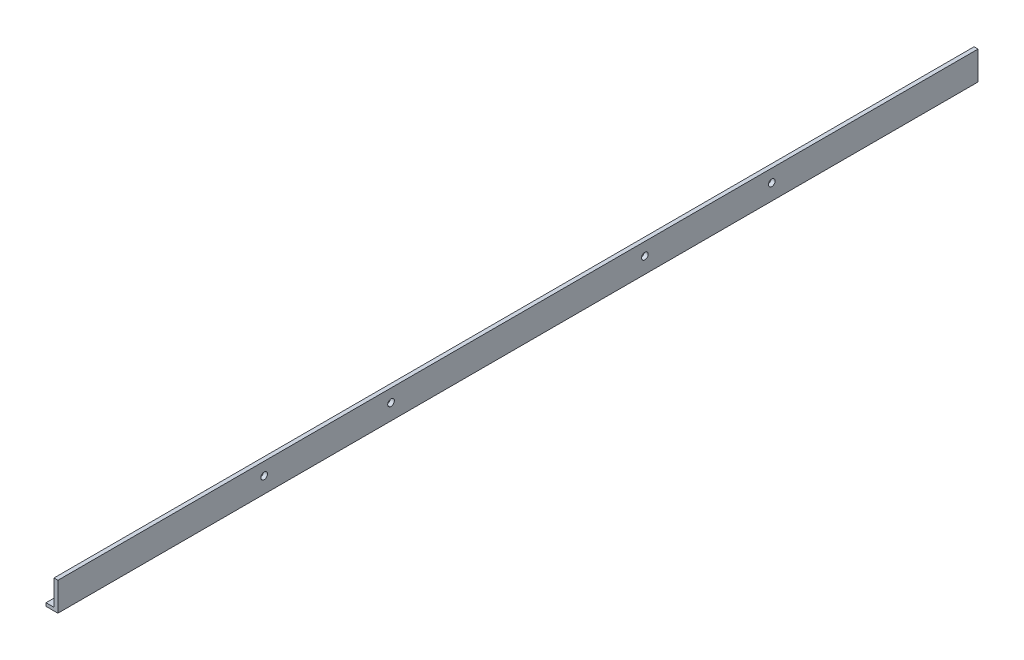
SolidWorks part; units mm, degrees
material "1.4511 (X3CrNb17)"
ref_plane "前视基准面" through (0, 0, 0) normal (0, 0, 1) x (1, 0, 0)
ref_plane "上视基准面" through (0, 0, 0) normal (0, 1, 0) x (1, 0, 0)
ref_plane "右视基准面" through (0, 0, 0) normal (1, 0, 0) x (0, 0, -1)
sketch "草图1" plane through (0, 0, 0) normal (0, 0, 1) x (1, 0, 0)
  line L0 (0, 0) -> (0, 18)
  line L1 (0, 18) -> (-2.5, 18)
  line L2 (-2.5, 18) -> (-2.5, 2)
  line L3 (-2.5, 2) -> (-7.5, 2)
  line L4 (-7.5, 2) -> (-7.5, 0)
  line L5 (-7.5, 0) -> (0, 0)
  dimension "D1" = 18
  dimension "D2" = 2.5
  dimension "D3" = 16
  dimension "D4" = 5
extrude "凸台-拉伸1" add sketch "草图1" along normal blind 580
sketch "草图2" plane through (-2.5, 0, 0) normal (-1, 0, 0) x (0, 0, 1)
  line L0 (290, 18) -> (290, 2) construction
  line L1 (580, 18) -> (0, 18) construction
  line L2 (580, 2) -> (0, 2) construction
  line L3 (130, 10) -> (450, 10) construction
  line L4 (210, 10) -> (370, 10) construction
  line L5 (580, 0) -> (0, 0) construction
  point P12 (290, 10)
  point P13 (290, 10)
  dimension "D1" = 320
  dimension "D2" = 160
  dimension "D3" = 10
  dimension "D4" = 10
hole_wizard "M5 螺纹孔1" positions "草图3" profile "草图4" tap size "M5" standard "GB" end condition through all
sketch "草图3" plane through (-2.5, 0, 0) normal (-1, 0, 0) x (0, 0, 1)
  point P0 (130, 10)
  point P3 (210, 10)
  point P6 (370, 10)
  point P9 (450, 10)
sketch "草图4" plane through (-2.5, 10, 130) normal (0, 1, 0) x (0, 0, 1)
  line L0 (0, 0) -> (0, 2.5)
  line L1 (0, 2.5) -> (2.1, 2.5)
  line L2 (2.1, 2.5) -> (2.1, 0)
  line L5 (2.1, 0) -> (0, 0)
  line L11 (0, -6.35) -> (0, 107.95) construction
  dimension "通孔螺纹孔钻头直径" = 4.2
  dimension "通孔螺纹孔钻头深度" = 2.5
cosmetic thread "孔螺蚊线1"
cosmetic thread "孔螺蚊线2"
cosmetic thread "孔螺蚊线3"
cosmetic thread "孔螺蚊线4"
